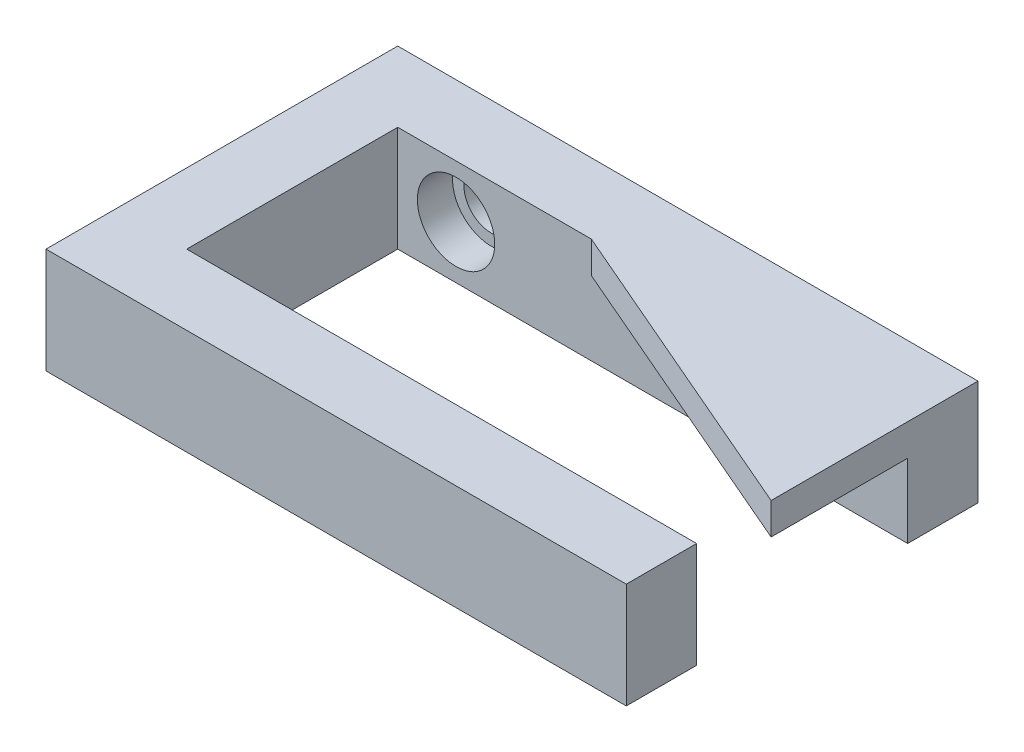
SolidWorks part; units mm, degrees
ref_plane "Ön Düzlem" through (0, 0, 0) normal (0, 0, 1) x (1, 0, 0)
ref_plane "Üst Düzlem" through (0, 0, 0) normal (0, 1, 0) x (1, 0, 0)
ref_plane "Sağ Düzlem" through (0, 0, 0) normal (1, 0, 0) x (0, 0, -1)
sketch "Çizim1" plane through (0, 0, 0) normal (0, 1, 0) x (1, 0, 0)
  line L0 (-20, 80) -> (260, 80)
  line L1 (0, 0) -> (240, 0)
  line L2 (0, 0) -> (0, 60)
  line L3 (0, 60) -> (240, 60)
  line L4 (240, 0) -> (240, 60)
  line L5 (260, -20) -> (260, 80)
  line L6 (-20, -20) -> (260, -20)
  line L7 (-20, -20) -> (-20, 80)
  dimension "D1" = 60
  dimension "D2" = 240
  dimension "D3" = 20
extrude "Yükseklik-Ekstrüzyon1" add sketch "Çizim1" along normal blind 30
sketch "Çizim2" plane through (0, 0, 0) normal (0, -1, 0) x (-1, 0, 0)
  line L0 (0, 0) -> (20, -20) construction
  line L1 (15, -20) -> (15, 9.3947) construction
  line L2 (20, -20) -> (-260, -20) construction
  line L3 (20, -15) -> (0, -15) construction
  line L4 (20, 80) -> (20, -20) construction
  line L5 (-120, -20) -> (-120, 658.3884) construction
  line L6 (-240, 30) -> (0, 30) construction
  line L7 (-240, 0) -> (-240, 60) construction
  line L8 (0, 60) -> (0, 0) construction
  circle A0 centre (10, -10) radius 7.5
  circle A1 centre (-250, -10) radius 7.5
  circle A2 centre (10, 70) radius 7.5
  circle A3 centre (-250, 70) radius 7.5
  circle A4 centre (-120, -10) radius 7.5
  circle A5 centre (-120, 70) radius 7.5
  dimension "D1" = 15
  dimension "D2" = 15
  dimension "D3" = 15
sketch "Çizim3" plane through (0, 0, 20) normal (0, 0, 1) x (1, 0, 0)
  line L0 (-20, 15) -> (37.6853, 15) construction
  line L1 (-20, 30) -> (-20, 0) construction
  line L2 (120, 30) -> (120, -4.2908) construction
  line L3 (-20, 30) -> (260, 30) construction
  circle A0 centre (16.5795, 15) radius 11
  circle A1 centre (228.0369, 15) radius 11
  circle A2 centre (95.4699, 15) radius 11
  dimension "D1" = 22
ref_plane "Düzlem1" through (0, 0, -30) normal (0, 0, 1) x (1, 0, 0)
sketch "Çizim4" plane through (0, 0, -30) normal (0, 0, 1) x (1, 0, 0)
  circle A0 centre (228.0369, 15) radius 11
  circle A1 centre (16.5795, 15) radius 11
  circle A2 centre (95.4699, 15) radius 11
extrude "Kes-Ekstrüzyon1" cut sketch "Çizim4" against normal mid plane 80
sketch "Çizim5" plane through (0, 0, 20) normal (0, 0, 1) x (1, 0, 0)
  line L0 (144.9782, 30) -> (144.9782, 15)
  line L1 (-20, 30) -> (260, 30) construction
  line L2 (-20, 15) -> (37.6853, 15) construction
  line L3 (144.9782, 15) -> (209.9782, 15)
  line L4 (209.9782, 15) -> (209.9782, 30)
  line L6 (144.9782, 30) -> (209.9782, 30)
  dimension "D1" = 65
extrude "Kes-Ekstrüzyon2" cut sketch "Çizim5" against normal blind 119 contours L3 L4 L6 L0
sketch "Çizim6" plane through (0, 0, -30) normal (0, 0, 1) x (1, 0, 0)
  line L0 (234.3599, 20.4676) -> (260, 4.8011)
  line L1 (260, 4.8011) -> (234.3599, 20.4676)
  line L2 (260, 4.8011) -> (260, 31.5523)
  line L3 (260, 31.5523) -> (234.1332, 31.5523)
  line L4 (234.1332, 31.5523) -> (234.3599, 20.4676)
  line L5 (260, 30) -> (260, 0) construction
extrude "Kes-Ekstrüzyon3" cut sketch "Çizim6" against normal mid plane 49 contours L3 L4 L0 L2
sketch "Çizim7" plane through (0, 0, -30) normal (0, 0, 1) x (1, 0, 0)
  circle A0 centre (228.0369, 15) radius 4
  circle A1 centre (95.4699, 15) radius 4
  dimension "D1" = 8
  dimension "D2" = 8
ref_plane "Düzlem2" through (0, 22, 0) normal (0, 1, 0) x (1, 0, 0)
sketch "Çizim10" plane through (0, 22, 0) normal (0, 1, 0) x (1, 0, 0)
  line L0 (55.057, 60) -> (144.9782, 21.1759)
  line L1 (144.9782, 60) -> (0, 60) construction
  line L3 (144.9782, 21.1759) -> (144.9782, 60)
  line L4 (144.9782, 60) -> (55.057, 60)
  line L5 (0, 0) -> (144.9782, 0) construction
  dimension "D1" = 21.1759
extrude "Yükseklik-Ekstrüzyon4" add sketch "Çizim10" along normal blind 8 and the other way blind 1
sketch "Çizim13" plane through (0, 0, -80) normal (0, 0, -1) x (-1, 0, 0)
  circle A0 centre (-16.5795, 15) radius 7.75
  dimension "D1" = 15.5
extrude "Kes-Ekstrüzyon4" cut sketch "Çizim13" against normal blind 18
sketch "Çizim14" plane through (0, 30, 0) normal (0, 1, 0) x (1, 0, 0)
  line L1 (279.0479, 84.6413) -> (144.9782, 84.6413)
  line L2 (279.0479, 84.6413) -> (279.0479, -20)
  line L3 (279.0479, -20) -> (144.9782, -20)
  line L4 (144.9782, 84.6413) -> (144.9782, -20)
extrude "Kes-Ekstrüzyon7" cut sketch "Çizim14" against normal blind 136
